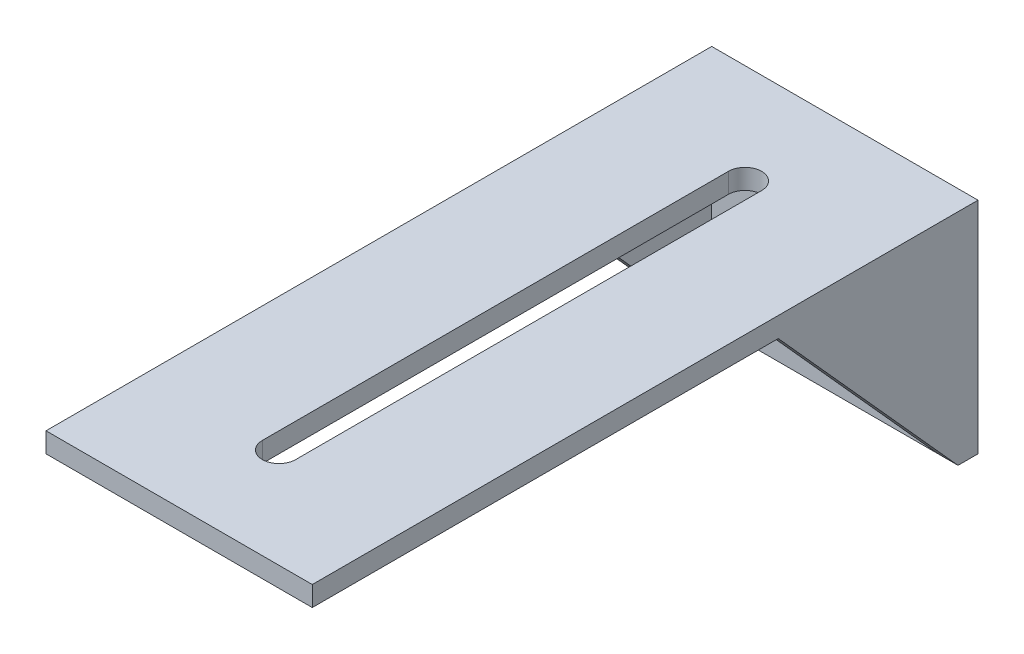
SolidWorks part; units mm, degrees
ref_plane "Front Plane" through (0, 0, 0) normal (0, 0, 1) x (1, 0, 0)
ref_plane "Top Plane" through (0, 0, 0) normal (0, 1, 0) x (1, 0, 0)
ref_plane "Right Plane" through (0, 0, 0) normal (1, 0, 0) x (0, 0, -1)
sketch "Sketch1" plane through (0, 0, 0) normal (0, 1, 0) x (1, 0, 0)
  line L0 (20, -85) -> (20, -15) construction
  line L1 (0, 0) -> (40, 0)
  line L2 (0, 0) -> (0, -100)
  line L3 (0, -100) -> (40, -100)
  line L4 (40, 0) -> (40, -100)
  line L5 (17.5, -85) -> (17.5, -15)
  line L6 (22.5, -85) -> (22.5, -15)
  arc A0 (17.5, -85) -> (22.5, -85) centre (20, -85) ccw
  arc A1 (22.5, -15) -> (17.5, -15) centre (20, -15) ccw
  point P7 (20, -50)
  point P14 (20.7376, -150)
  dimension "D3" = 20
  dimension "D1" = 100
  dimension "D2" = 40
  dimension "D4" = 15
  dimension "D5" = 15
extrude "Boss-Extrude1" add sketch "Sketch1" along normal blind 3
sketch "Sketch2" plane through (0, 0, 0) normal (0, -1, 0) x (1, 0, 0)
  line L0 (40, 100) -> (40, 0) construction
  line L1 (0, 0) -> (40, 0)
  line L2 (0, 0) -> (0, 3)
  line L3 (0, 3) -> (40, 3)
  line L4 (40, 0) -> (40, 3)
  dimension "D1" = 3
extrude "Boss-Extrude2" add sketch "Sketch2" along normal blind 30
chamfer "Chamfer1" distance 5 angle 45 1 edges
sketch "Sketch3" plane through (0, 0, 0) normal (0, 0, -1) x (-1, 0, 0)
  line L0 (-40, 3) -> (0, 3) construction
  line L1 (0, -30) -> (-3, -30)
  line L2 (0, -30) -> (0, 3)
  line L3 (0, 3) -> (-3, 3)
  line L4 (-3, -30) -> (-3, 3)
  line L5 (0, -30) -> (-40, -30) construction
  line L6 (-40, 3) -> (-37, 3)
  line L7 (-40, 3) -> (-40, -30)
  line L8 (-40, -30) -> (-37, -30)
  line L9 (-37, 3) -> (-37, -30)
  dimension "D1" = 3
  dimension "D2" = 3
extrude "Boss-Extrude3" add sketch "Sketch3" against normal blind 30
sketch "Sketch4" plane through (3, 0, 0) normal (1, 0, 0) x (0, 0, -1)
  line L0 (-30, 0) -> (-3, -30)
  line L1 (-3, -30) -> (-30, -30)
  line L2 (-30, -30) -> (-30, 0)
extrude "Cut-Extrude1" cut sketch "Sketch4" against normal blind 30 and the other way blind 50
sketch "Sketch5" plane through (0, 0, 3) normal (0, 0, 1) x (1, 0, 0)
  line L0 (0, 0) -> (0, -30) construction
  circle A0 centre (20, -16.4953) radius 1.75
  dimension "D1" = 20
extrude "Cut-Extrude2" cut sketch "Sketch5" against normal blind 30
